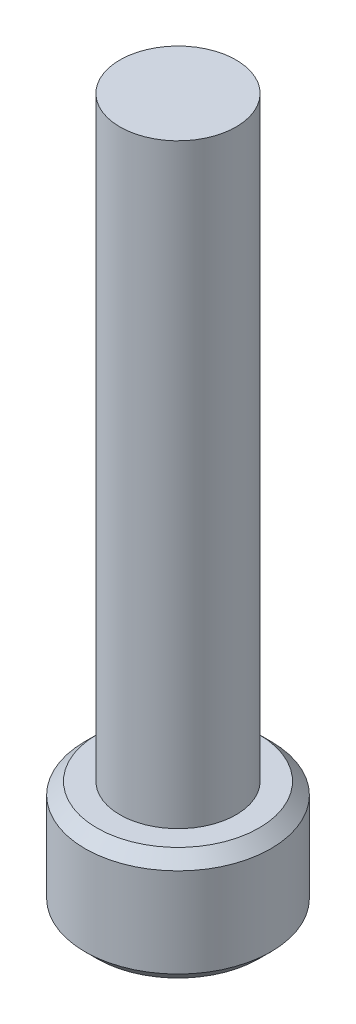
SolidWorks part; units mm, degrees
ref_plane "Front Plane" through (0, 0, 0) normal (0, 0, 1) x (1, 0, 0)
ref_plane "Top Plane" through (0, 0, 0) normal (0, 1, 0) x (1, 0, 0)
ref_plane "Right Plane" through (0, 0, 0) normal (1, 0, 0) x (0, 0, -1)
sketch "Sketch1" plane through (0, 0, 0) normal (0, 1, 0) x (1, 0, 0)
  circle A0 centre (0, 0) radius 2.4765
  dimension "D1" = 4.953
extrude "Boss-Extrude1" add sketch "Sketch1" along normal blind 25.4
sketch "Sketch2" plane through (0, 0, 0) normal (0, -1, 0) x (1, 0, 0)
  circle A0 centre (0, 0) radius 3.9624
  dimension "D1" = 7.9248
extrude "Boss-Extrude2" add sketch "Sketch2" along normal blind 4.826
sketch "Sketch3" plane through (0, -4.826, 0) normal (0, -1, 0) x (1, 0, 0)
  line L1 (2.2914, 0) -> (1.1457, 1.9844)
  line L2 (1.1457, 1.9844) -> (-1.1457, 1.9844)
  line L3 (-1.1457, 1.9844) -> (-2.2914, 0)
  line L4 (-2.2914, 0) -> (-1.1457, -1.9844)
  line L5 (-1.1457, -1.9844) -> (1.1457, -1.9844)
  line L6 (1.1457, -1.9844) -> (2.2914, 0)
  circle A0 centre (0, 0) radius 1.9844 construction
  dimension "D1" = 3.9688
extrude "Cut-Extrude1" cut sketch "Sketch3" against normal blind 2.286
chamfer "Chamfer1" distance 0.508 angle 45 2 edges at (0, -4.826, -3.9624) (0, 0, -3.9624)
